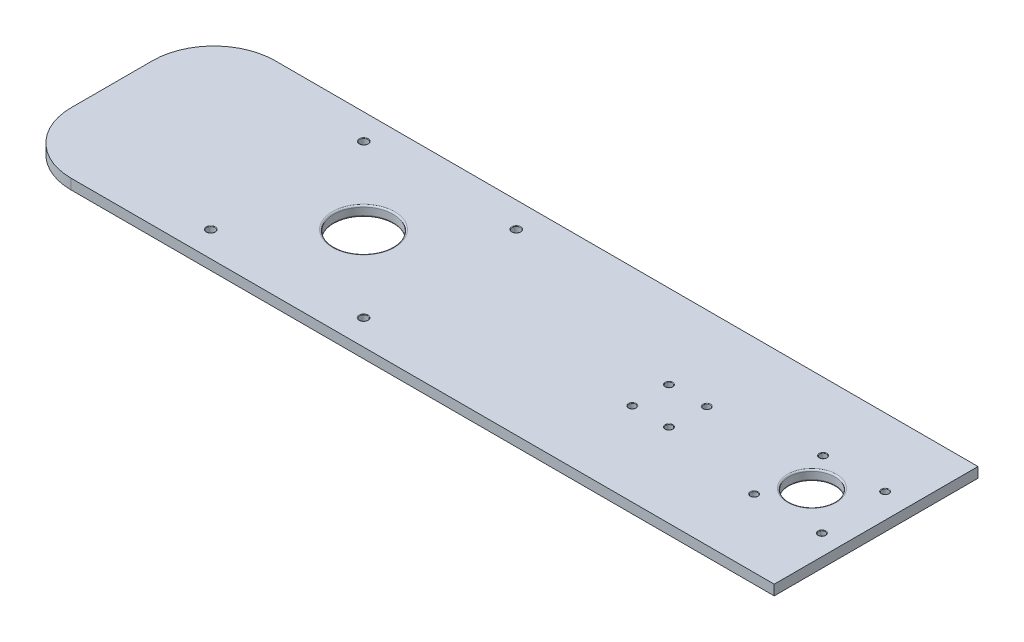
SolidWorks part; units mm, degrees
ref_plane "Front Plane" through (0, 0, 0) normal (0, 0, 1) x (1, 0, 0)
ref_plane "Top Plane" through (0, 0, 0) normal (0, 1, 0) x (1, 0, 0)
ref_plane "Right Plane" through (0, 0, 0) normal (1, 0, 0) x (0, 0, -1)
sketch "Sketch3" plane through (0, 0, 0) normal (0, 1, 0) x (1, 0, 0)
  line L1 (-375, 100) -> (375, 100)
  line L2 (-375, 100) -> (-375, -100)
  line L3 (-375, -100) -> (375, -100)
  line L4 (375, 100) -> (375, -100)
  line L5 (-375, 100) -> (375, -100) construction
  line L6 (-375, -100) -> (375, 100) construction
  point P0 (0, 0)
  dimension "D1" = 750
  dimension "D2" = 200
extrude "Boss-Extrude1" add sketch "Sketch3" along normal blind 10
sketch "Sketch6" plane through (0, 10, 0) normal (0, 1, 0) x (1, 0, 0)
  line L1 (-375, -100) -> (375, -100) construction
  line L2 (375, -100) -> (375, 100) construction
  circle A0 centre (-128, -0.0934) radius 29
  circle A1 centre (153.6966, -18) radius 3.4
  circle A2 centre (153.6966, 18) radius 3.4
  circle A3 centre (190.8676, 17.9809) radius 3.4
  circle A4 centre (189.6966, -18) radius 3.4
  circle A5 centre (288.53, -33.23) radius 3.4
  circle A6 centre (289.6966, 33.24) radius 3.4
  circle A7 centre (350.6192, 33.24) radius 3.4
  circle A8 centre (355, -33.23) radius 3.4
  circle A9 centre (312, 0) radius 22.5
  circle A10 centre (-53, -75) radius 4
  circle A11 centre (-203, -75) radius 4
  circle A12 centre (-202.8129, 75) radius 4
  circle A13 centre (-53.187, 75) radius 4
  point P2 (195, -0.0934)
  point P3 (-128, -0.0934)
  point P35 (0, 0)
  dimension "D1" = 58
  dimension "D5" = 6.8
  dimension "D6" = 82
  dimension "D7" = 6.8
  dimension "D8" = 36
  dimension "D9" = 6.8
  dimension "D10" = 6.8
  dimension "D12" = 36
  dimension "D13" = 36
  dimension "D14" = 6.8
  dimension "D15" = 6.8
  dimension "D16" = 6.8
  dimension "D17" = 6.8
  dimension "D18" = 100
  dimension "D19" = 20
  dimension "D20" = 66.47
  dimension "D21" = 100
  dimension "D22" = 60.9226
  dimension "D23" = 66.77
  dimension "D24" = 66.77
  dimension "D25" = 66.47
  dimension "D26" = 66.47
  dimension "D27" = 45
  dimension "D28" = 100
  dimension "D29" = 63
  dimension "D30" = 8
  dimension "D31" = 25
  dimension "D32" = 106
  dimension "D33" = 8
  dimension "D34" = 8
  dimension "D37" = 106
  dimension "D38" = 150
  dimension "D40" = 8
  dimension "D2" = 323
  dimension "D3" = 128
  dimension "D4" = 0
  dimension "D11" = 82
  dimension "D35" = 150
  dimension "D36" = 25
  dimension "D39" = 106
  dimension "D41" = 150
  dimension "D42" = 106
extrude "Cut-Extrude1" cut sketch "Sketch6" against normal blind 20
fillet "Fillet6" radius 60 2 edges at (-375, 5, 100) (-375, 5, -100)
fillet "Fillet7" radius 0.5 24 edges at (288.53, 10, 36.63) (355, 10, 36.63) (350.6192, 10, -29.84) (289.6966, 10, -29.84) (189.6966, 10, 21.4) (190.8676, 10, -14.5809) (153.6966, 10, -14.6) (153.6966, 10, 21.4) (-53, 10, 79) (-203, 10, 79) (-53.187, 10, -71) (-202.8129, 10, -71) (288.53, 0, 36.63) (355, 0, 36.63) (350.6192, 0, -29.84) (289.6966, 0, -29.84) (153.6966, 0, -14.6) (153.6966, 0, 21.4) (189.6966, 0, 21.4) (190.8676, 0, -14.5809) (-53, 0, 79) (-53.187, 0, -71) (-202.8129, 0, -71) (-203, 0, 79)
fillet "Fillet8" radius 1.5 4 edges at (312, 10, 22.5) (312, 0, 22.5) (-128, 10, 29.0934) (-128, 0, 29.0934)
